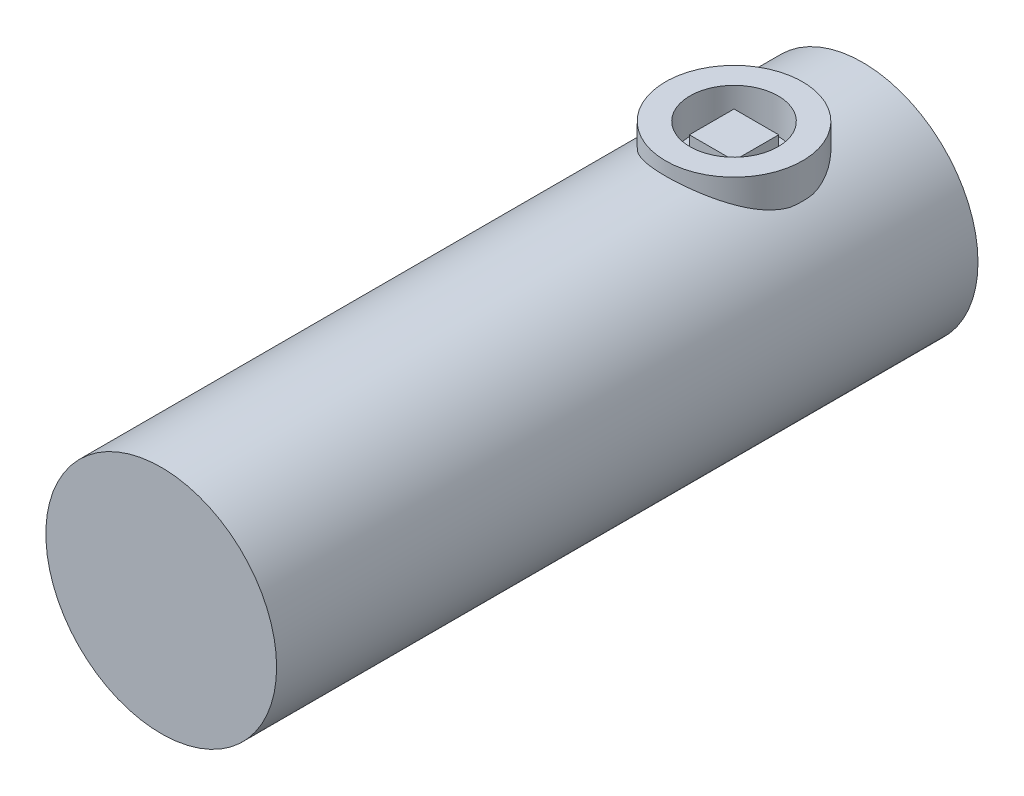
SolidWorks part; units mm, degrees
ref_plane "Front Plane" through (0, 0, 0) normal (0, 0, 1) x (1, 0, 0)
ref_plane "Top Plane" through (0, 0, 0) normal (0, 1, 0) x (1, 0, 0)
ref_plane "Right Plane" through (0, 0, 0) normal (1, 0, 0) x (0, 0, -1)
sketch "Sketch1" plane through (0, 0, 0) normal (0, 0, 1) x (1, 0, 0)
  circle A0 centre (0, 0) radius 12.5349
  dimension "D1" = 25.0698
extrude "Boss-Extrude1" add sketch "Sketch1" along normal blind 76.2
ref_plane "Plane1" through (0, 10.16, 0) normal (0, 1, 0) x (1, 0, 0)
sketch "Sketch2" plane through (0, 10.16, 0) normal (0, 1, 0) x (1, 0, 0)
  line L0 (12.5349, 0) -> (-12.5349, 0) construction
  line L1 (12.5349, -76.2) -> (12.5349, 0) construction
  circle A0 centre (0, -13.97) radius 4.7879
  dimension "D1" = 9.5758
  dimension "D2" = 13.97
  dimension "D3" = 12.5349
extrude "Cut-Extrude1" cut sketch "Sketch2" along normal blind 76.2 contours A0
sketch "Sketch3" plane through (0, 10.16, 0) normal (0, 1, 0) x (1, 0, 0)
  line L1 (-2.4257, -16.3957) -> (2.4257, -16.3957)
  line L2 (-2.4257, -16.3957) -> (-2.4257, -11.5443)
  line L3 (-2.4257, -11.5443) -> (2.4257, -11.5443)
  line L4 (2.4257, -16.3957) -> (2.4257, -11.5443)
  line L5 (-2.4257, -16.3957) -> (2.4257, -11.5443) construction
  line L6 (-2.4257, -11.5443) -> (2.4257, -16.3957) construction
  point P0 (0, -13.97)
  dimension "D1" = 4.8514
  dimension "D2" = 4.8514
extrude "Boss-Extrude2" add sketch "Sketch3" along normal blind 2.54
sketch "Sketch4" plane through (0, 10.16, 0) normal (0, 1, 0) x (1, 0, 0)
  circle A0 centre (0, -13.97) radius 4.7879
  circle A1 centre (0, -13.97) radius 7.4422
  dimension "D1" = 9.5758
  dimension "D2" = 14.8844
extrude "Boss-Extrude3" add sketch "Sketch4" along normal blind 3.81
